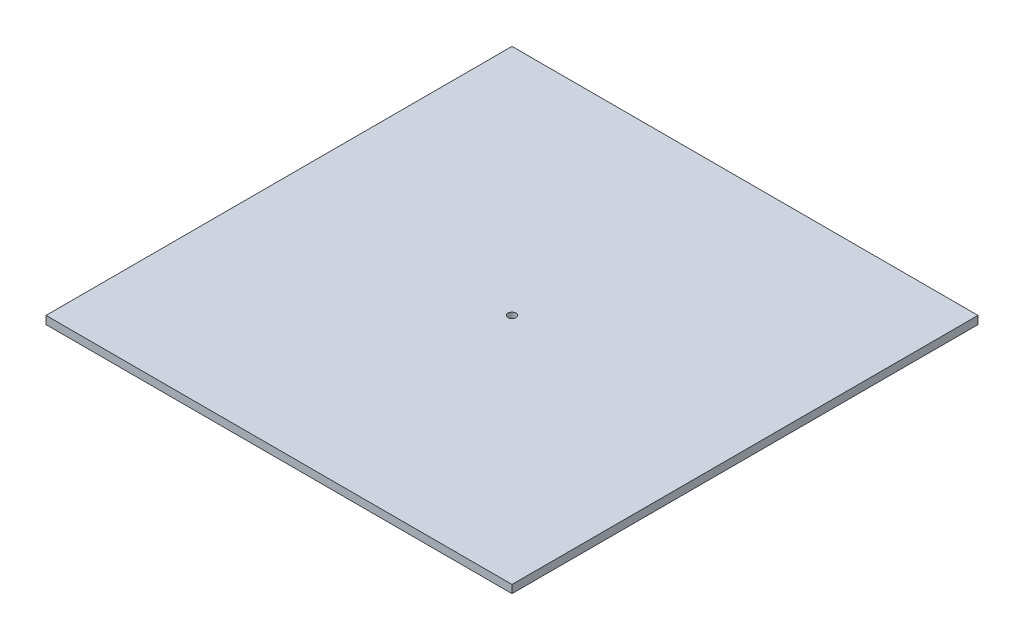
SolidWorks part; units mm, degrees
ref_plane "Plan de face" through (0, 0, 0) normal (0, 0, 1) x (1, 0, 0)
ref_plane "Plan de dessus" through (0, 0, 0) normal (0, 1, 0) x (1, 0, 0)
ref_plane "Plan de droite" through (0, 0, 0) normal (1, 0, 0) x (0, 0, -1)
sketch "Esquisse1" plane through (0, 0, 0) normal (0, 1, 0) x (1, 0, 0)
  line L1 (-175, -175) -> (175, -175)
  line L2 (-175, -175) -> (-175, 175)
  line L3 (-175, 175) -> (175, 175)
  line L4 (175, -175) -> (175, 175)
  line L5 (-175, -175) -> (175, 175) construction
  line L6 (-175, 175) -> (175, -175) construction
  point P0 (0, 0)
  dimension "D1" = 350
extrude "Boss.-Extru.1" add sketch "Esquisse1" along normal blind 6
sketch "Esquisse2" plane through (0, 6, 0) normal (0, 1, 0) x (1, 0, 0)
  circle A0 centre (0, 0) radius 3
  dimension "D1" = 6
extrude "Enlèv. mat.-Extru.1" cut sketch "Esquisse2" against normal through all both and the other way through all
